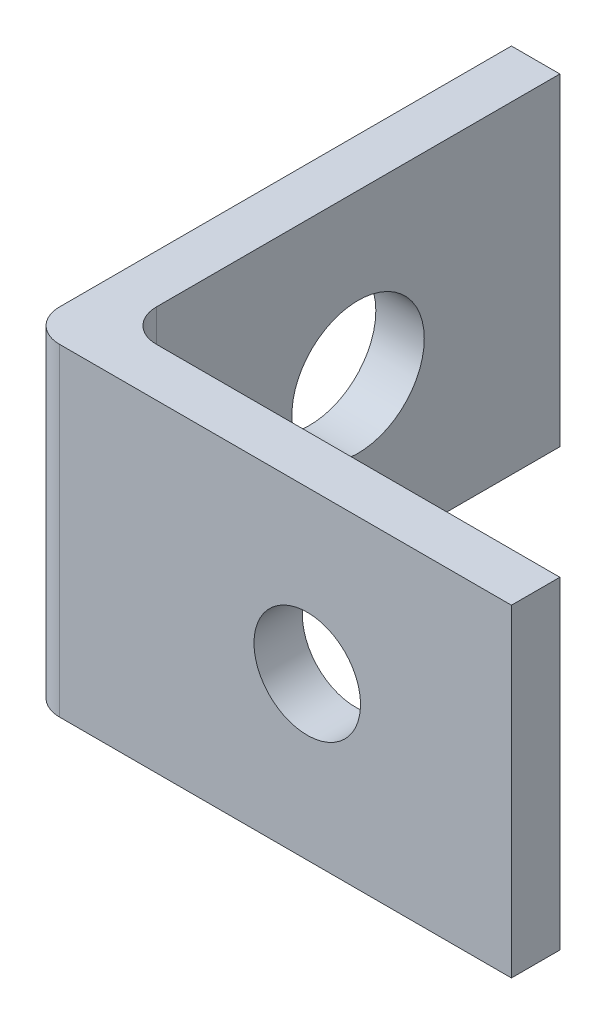
SolidWorks part; units mm, degrees
ref_plane "Спереди" through (0, 0, 0) normal (0, 0, 1) x (1, 0, 0)
ref_plane "Сверху" through (0, 0, 0) normal (0, 1, 0) x (1, 0, 0)
ref_plane "Справа" through (0, 0, 0) normal (1, 0, 0) x (0, 0, -1)
sketch "Эскиз1" plane through (0, 0, 0) normal (0, 1, 0) x (1, 0, 0)
  line L0 (0, 1) -> (0, 15)
  line L5 (0, 15) -> (1.5, 15)
  line L6 (1, 0) -> (15, 0)
  line L7 (15, 0) -> (15, 1.5)
  line L8 (15, 1.5) -> (2.5, 1.5)
  line L9 (1.5, 2.5) -> (1.5, 15)
  arc A0 (1, 0) -> (0, 1) centre (1, 1) cw
  arc A1 (2.5, 1.5) -> (1.5, 2.5) centre (2.5, 2.5) cw
  point P0 (0, 0)
  point P10 (0, 0)
  dimension "D5" = 1
  dimension "D1" = 15
  dimension "D2" = 1.5
  dimension "D3" = 15
  dimension "D4" = 1.5
extrude "Бобышка-Вытянуть1" add sketch "Эскиз1" along normal blind 10
sketch "Эскиз2" plane through (0, 0, 0) normal (0, 0, 1) x (1, 0, 0)
  line L0 (8.25, 0) -> (8.25, 11.3489) construction
  line L3 (1, 0) -> (15, 0) construction
  line L4 (15, 10) -> (15, 0) construction
  dimension "D1" = 6.75
sketch "Эскиз3" plane through (0, 0, 0) normal (-1, 0, 0) x (0, 0, 1)
  line L0 (-8.25, 0) -> (-8.25, 11.1434) construction
  line L1 (-15, 0) -> (-1, 0) construction
  dimension "D1" = 6.75
extrude "Вырез-Вытянуть3" cut sketch "Эскиз6" against normal blind 8 contours L4 A0 | A0 L4
sketch "Эскиз6" plane through (-307.9408, -349.2045, -1.5) normal (0, 0, -1) x (-0.9999, 0.0149, 0)
  line L2 (-317.5586, 363.9713) -> (-305.06, 363.7853)
  line L3 (-317.7074, 353.9725) -> (-305.2088, 353.7864)
  line L4 (-311.3093, 363.8783) -> (-311.3093, 353.8772) construction
  circle A0 centre (-311.3093, 358.8778) radius 1.65
sketch "Эскиз12" plane through (1.5, 0, 0) normal (1, 0, 0) x (0, 0, -1)
  line L0 (8.75, 10) -> (8.75, 0) construction
  line L4 (2.5, 0) -> (15, 0)
  line L5 (15, 0) -> (15, 10)
  line L6 (15, 10) -> (2.5, 10)
  line L7 (2.5, 10) -> (2.5, 0)
  line L8 (2.5, 0) -> (15, 0) construction
  line L9 (15, 0) -> (15, 10) construction
  line L10 (15, 10) -> (2.5, 10) construction
  line L11 (2.5, 10) -> (2.5, 0) construction
  circle A0 centre (8.75, 5) radius 2.05
  dimension "D1" = 0
extrude "Вырез-Вытянуть5" cut sketch "Эскиз12" against normal blind 95
